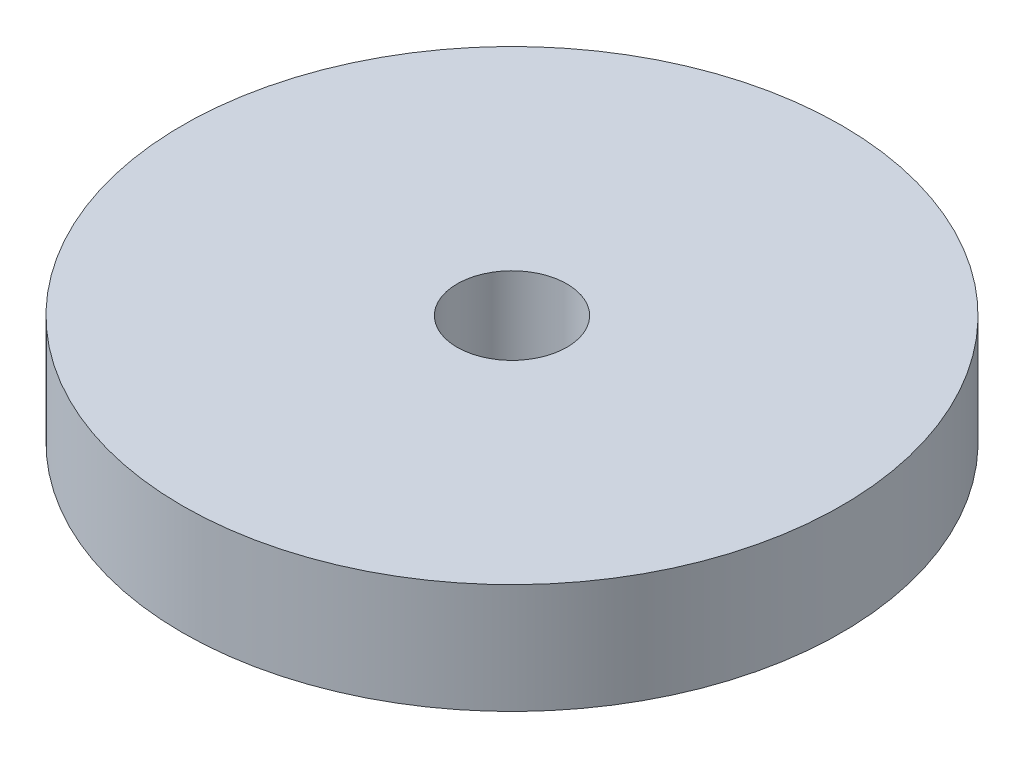
SolidWorks part; units mm, degrees
ref_plane "Front Plane" through (0, 0, 0) normal (0, 0, 1) x (1, 0, 0)
ref_plane "Top Plane" through (0, 0, 0) normal (0, 1, 0) x (1, 0, 0)
ref_plane "Right Plane" through (0, 0, 0) normal (1, 0, 0) x (0, 0, -1)
sketch "Sketch1" plane through (0, 0, 0) normal (0, 1, 0) x (1, 0, 0)
  circle A0 centre (0, 0) radius 15
  dimension "D1" = 30
extrude "Boss-Extrude1" add sketch "Sketch1" along normal blind 5
sketch "Sketch2" plane through (0, 5, 0) normal (0, 1, 0) x (1, 0, 0)
  circle A0 centre (0, 0) radius 2.5
  dimension "D1" = 5
extrude "Cut-Extrude1" cut sketch "Sketch2" against normal up to next
